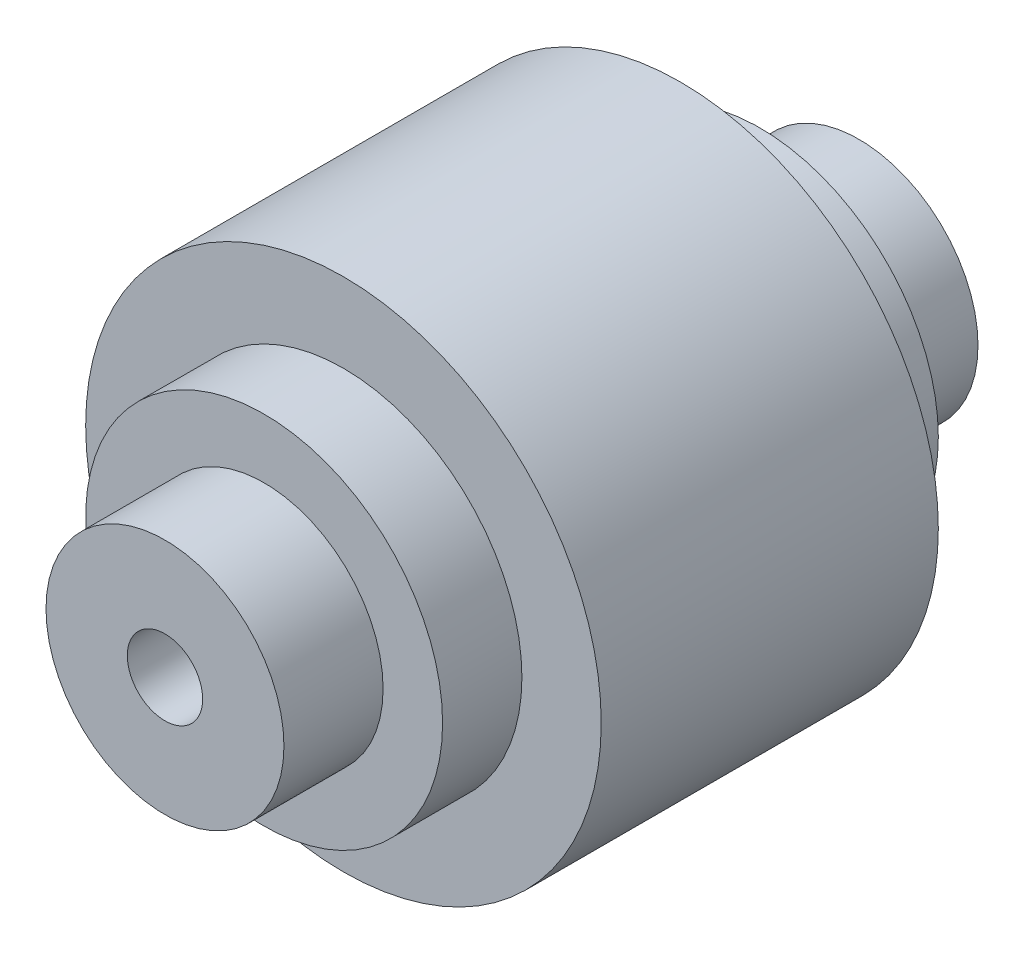
SolidWorks part; units mm, degrees
ref_plane "前视基准面" through (0, 0, 0) normal (0, 0, 1) x (1, 0, 0)
ref_plane "上视基准面" through (0, 0, 0) normal (0, 1, 0) x (1, 0, 0)
ref_plane "右视基准面" through (0, 0, 0) normal (1, 0, 0) x (0, 0, -1)
sketch "草图1" plane through (0, 0, 0) normal (0, 1, 0) x (1, 0, 0)
  line L0 (0, 0) -> (0, -35)
  line L1 (9, -9) -> (13, -9)
  line L2 (9, -26) -> (7.5, -26)
  line L3 (0, -17.5) -> (33.1572, -17.5) construction
  line L4 (6, -30) -> (6, -35)
  line L5 (6, -35) -> (0, -35)
  line L6 (7.5, -26) -> (7.5, -30)
  line L7 (7.5, -30) -> (6, -30)
  line L8 (9, -26) -> (13, -26)
  line L9 (13, -26) -> (13, -9)
  line L10 (7.5, -5) -> (6, -5)
  line L11 (7.5, -9) -> (7.5, -5)
  line L12 (6, 0) -> (0, 0)
  line L13 (6, -5) -> (6, 0)
  line L14 (9, -9) -> (7.5, -9)
  point P10 (13, -17.5)
revolve "旋转1" add sketch "草图1" angle 360 about L0
sketch "草图2" plane through (0, 0, 35) normal (0, 0, 1) x (1, 0, 0)
  circle A0 centre (0, 0) radius 1.9
extrude "切除-拉伸1" cut sketch "草图2" against normal blind 36
sketch "草图4" plane through (0, 0, 26) normal (0, 0, 1) x (1, 0, 0)
  circle A0 centre (0, 0) radius 9
  dimension "D1" = 18
extrude "凸台-拉伸1" add sketch "草图4" along normal blind 4 and the other way blind 21
